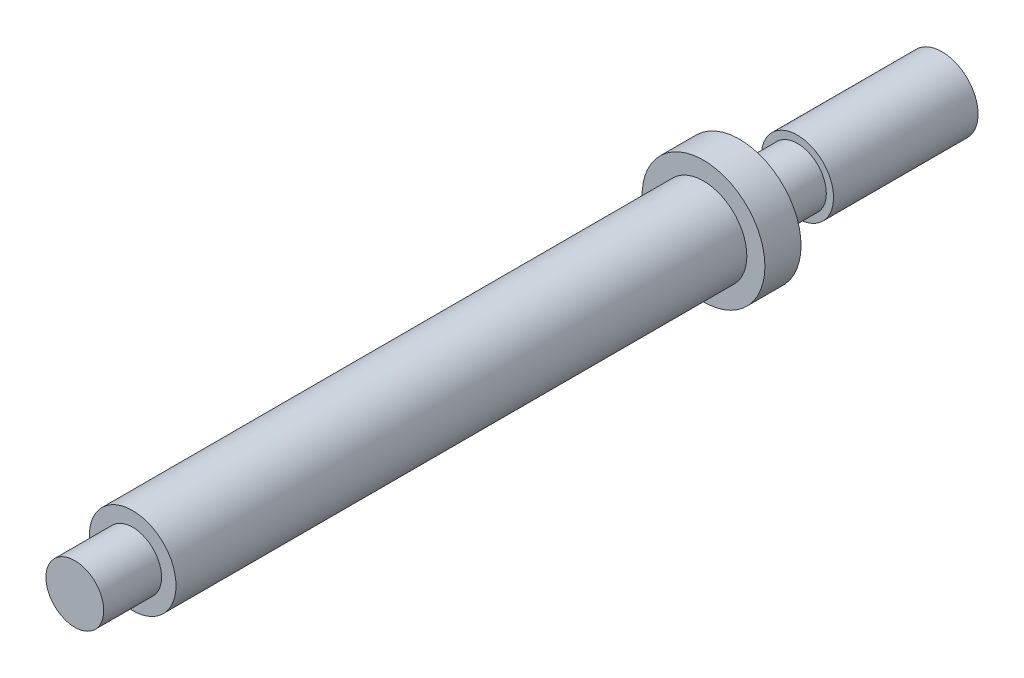
SolidWorks part; units mm, degrees
ref_plane "Front Plane" through (0, 0, 0) normal (0, 0, 1) x (1, 0, 0)
ref_plane "Top Plane" through (0, 0, 0) normal (0, 1, 0) x (1, 0, 0)
ref_plane "Right Plane" through (0, 0, 0) normal (1, 0, 0) x (0, 0, -1)
sketch "Sketch2" plane through (0, 0, 0) normal (1, 0, 0) x (0, 0, -1)
  line L0 (0, 0) -> (100, 0) construction
  line L1 (0, 0) -> (0, 4)
  line L2 (0, 4) -> (8, 4)
  line L3 (8, 4) -> (8, 6)
  line L4 (8, 6) -> (87, 6)
  line L5 (87, 6) -> (87, 8.5)
  line L6 (87, 8.5) -> (92, 8.5)
  line L7 (92, 8.5) -> (92, 4)
  line L8 (92, 4) -> (100, 4)
  line L9 (100, 4) -> (100, 0)
  line L10 (0, 0) -> (100, 0)
  dimension "D1" = 8
  dimension "D2" = 12
  dimension "D3" = 17
  dimension "D4" = 8
  dimension "D5" = 84
  dimension "D6" = 8
  dimension "D7" = 8
  dimension "D8" = 79
revolve "Revolve1" add sketch "Sketch2" angle 360 about L0
sketch "Sketch3" plane through (0, 0, -100) normal (0, 0, -1) x (-1, 0, 0)
  circle A0 centre (0, 0) radius 5
  dimension "D1" = 10
extrude "Boss-Extrude1" add sketch "Sketch3" along normal blind 20
